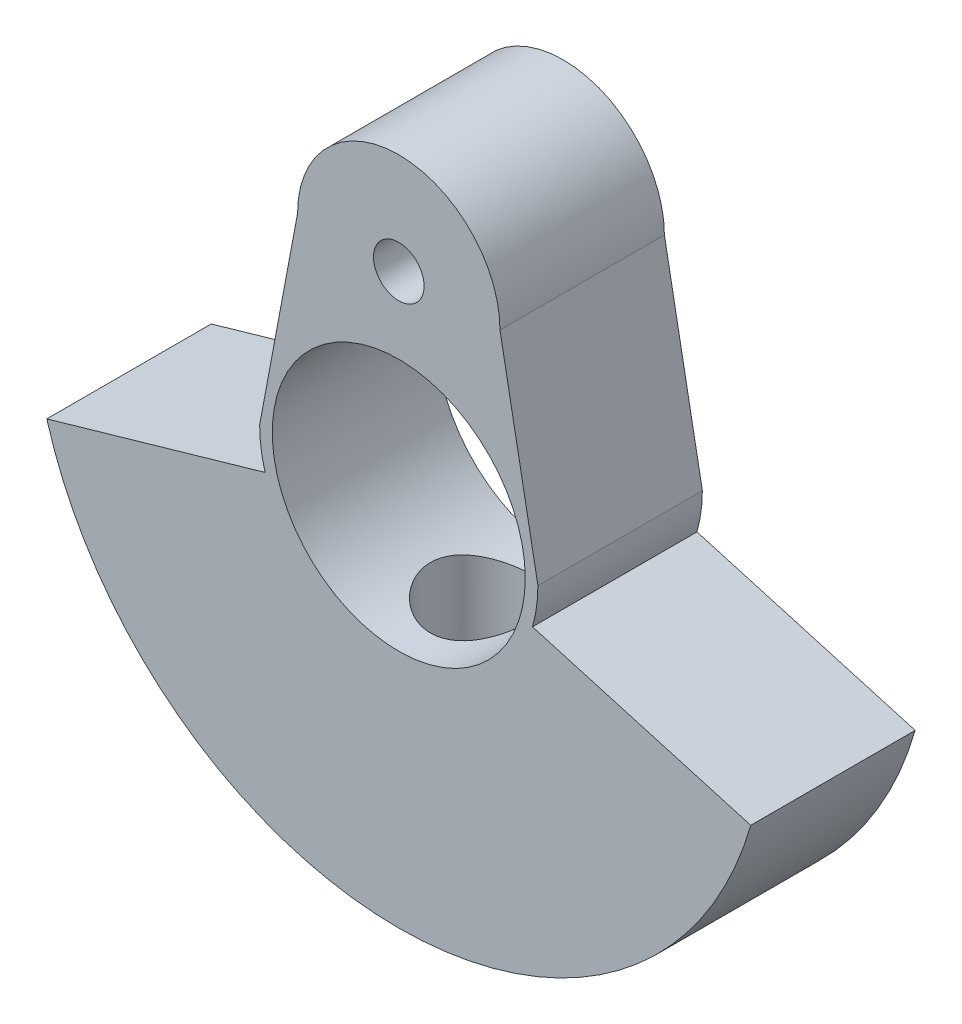
SolidWorks part; units mm, degrees
ref_plane "Front Plane" through (0, 0, 0) normal (0, 0, 1) x (1, 0, 0)
ref_plane "Top Plane" through (0, 0, 0) normal (0, 1, 0) x (1, 0, 0)
ref_plane "Right Plane" through (0, 0, 0) normal (1, 0, 0) x (0, 0, -1)
sketch "Sketch1" plane through (0, 0, 0) normal (0, 0, 1) x (1, 0, 0)
  line L3 (-5.2859, -1.5197) -> (-13.9131, -4)
  line L5 (5.2859, -1.5197) -> (13.9131, -4)
  line L6 (-4, 8) -> (-5.5, 0)
  line L7 (4, 8) -> (5.5, 0)
  arc A0 (5.1264, 1.9925) -> (-5.1264, 1.9925) centre (0, 0) ccw
  arc A1 (-13.9131, -4) -> (13.9131, -4) centre (0, 0) ccw
  circle A2 centre (0, 8) radius 1
  arc A3 (4, 8) -> (-4, 8) centre (0, 8) ccw
  arc A4 (-5.5, 0) -> (5.5, 0) centre (0, 0) ccw
  circle A5 centre (0, 0) radius 5
  dimension "D1" = 11
  dimension "D2" = 8
  dimension "D3" = 2
extrude "Boss-Extrude1" add sketch "Sketch1" along normal blind 6.5 contours A4 L3 A1 L5 | A5 | L7 A3 L6 A0 A2
hole_wizard "Ø4.0 (4) Diameter Hole1" positions "Sketch6" profile "Sketch5" hole size "Ø4.0" standard "ISO"
sketch "Sketch6" plane through (0, 0, 0) normal (0, 1, 0) x (1, 0, 0)
  line L0 (13.9131, 0) -> (-13.9131, 0) construction
  point P1 (0, -3.25)
  dimension "D1" = 3.25
sketch "Sketch5" plane through (0, 0, 3.25) normal (1, 0, 0) x (0, 0, 1)
  line L0 (0, 0) -> (0, 14.4766)
  line L1 (0, 14.4766) -> (2, 14.4766)
  line L2 (2, 14.4766) -> (2, 0)
  line L5 (2, 0) -> (0, 0)
  line L11 (0, -6.35) -> (0, 107.95) construction
  dimension "Thru Hole Dia." = 4
  dimension "Thru Hole Depth" = 14.4766
